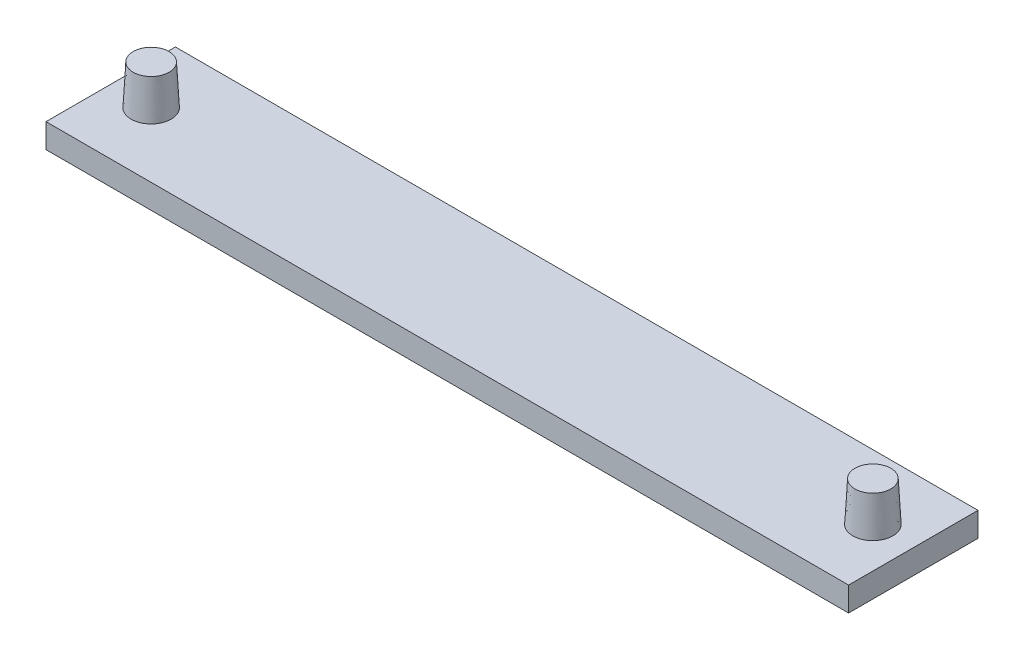
SolidWorks part; units mm, degrees
ref_plane "Front Plane" through (0, 0, 0) normal (0, 0, 1) x (1, 0, 0)
ref_plane "Top Plane" through (0, 0, 0) normal (0, 1, 0) x (1, 0, 0)
ref_plane "Right Plane" through (0, 0, 0) normal (1, 0, 0) x (0, 0, -1)
sketch "Sketch1" plane through (0, 0, 0) normal (0, 1, 0) x (1, 0, 0)
  line L0 (0.8266, 5.1023) -> (90.0766, 5.1023) construction
  line L2 (-4.1734, -2.8977) -> (95.0766, -2.8977)
  line L3 (-4.1734, -2.8977) -> (-4.1734, 13.1023)
  line L4 (-4.1734, 13.1023) -> (95.0766, 13.1023)
  line L5 (95.0766, -2.8977) -> (95.0766, 13.1023)
  dimension "D2" = 5
  dimension "D1" = 89.25
  dimension "D3" = 5
  dimension "D4" = 8
  dimension "D5" = 8
extrude "Boss-Extrude1" add sketch "Sketch1" along normal blind 3
sketch "Sketch2" plane through (0, 3, 0) normal (0, 1, 0) x (1, 0, 0)
  circle A0 centre (0.8266, 5.1023) radius 2.475
  circle A1 centre (90.0766, 5.1023) radius 2.475
  dimension "D1" = 4.95
  dimension "D2" = 4.95
extrude "Boss-Extrude2" add sketch "Sketch2" along normal blind 4.9 draft 3
